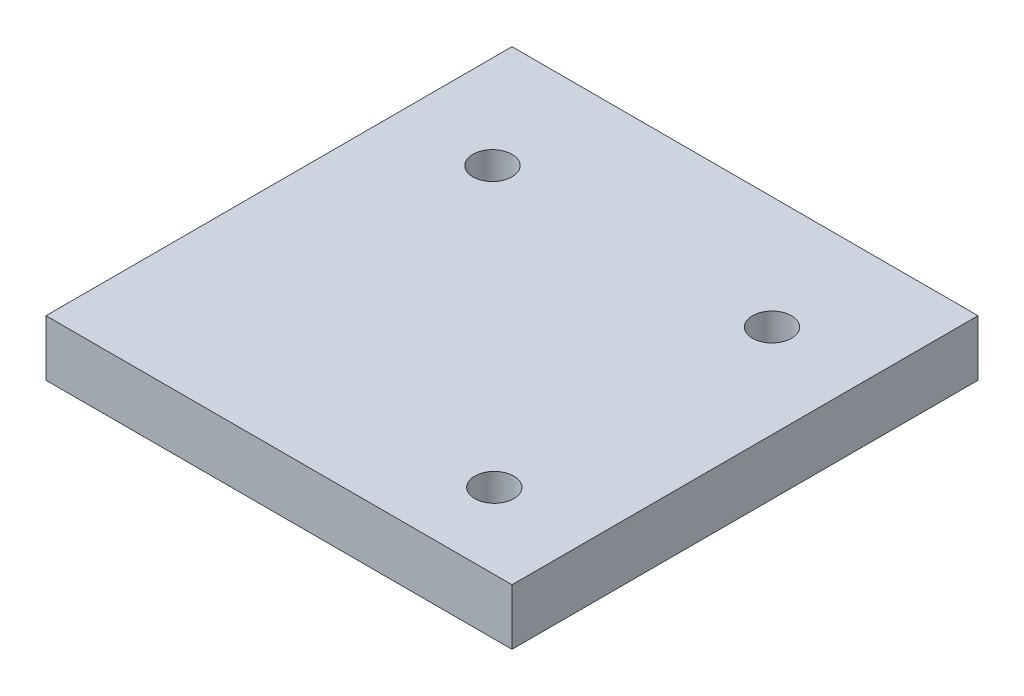
SolidWorks part; units mm, degrees
ref_plane "前视基准面" through (0, 0, 0) normal (0, 0, 1) x (1, 0, 0)
ref_plane "上视基准面" through (0, 0, 0) normal (0, 1, 0) x (1, 0, 0)
ref_plane "右视基准面" through (0, 0, 0) normal (1, 0, 0) x (0, 0, -1)
sketch "草图1" plane through (0, 0, 0) normal (0, 1, 0) x (1, 0, 0)
  line L1 (-25, -25) -> (25, -25)
  line L2 (-25, -25) -> (-25, 25)
  line L3 (-25, 25) -> (25, 25)
  line L4 (25, -25) -> (25, 25)
  line L5 (-25, -25) -> (25, 25) construction
  line L6 (-25, 25) -> (25, -25) construction
  point P0 (0, 0)
  dimension "D1" = 50
  dimension "D2" = 50
extrude "凸台-拉伸1" add sketch "草图1" along normal blind 6
sketch "草图2" plane through (0, 6, 0) normal (0, 1, 0) x (1, 0, 0)
  line L0 (-25, 12.9) -> (25, 12.9) construction
  line L1 (-25, 25) -> (-25, -25) construction
  line L2 (25, -25) -> (25, 25) construction
  line L3 (25, 25) -> (-25, 25) construction
  circle A0 centre (-15, 12.9) radius 2.1
  circle A1 centre (15, 12.9) radius 2.1
  dimension "D4" = 4.2
  dimension "D5" = 4.2
  dimension "D1" = 12.1
  dimension "D2" = 10
  dimension "D3" = 10
extrude "切除-拉伸1" cut sketch "草图2" against normal up to next
sketch "草图3" plane through (0, 6, 0) normal (0, 1, 0) x (1, 0, 0)
  line L0 (15, 12.9) -> (15, -25) construction
  line L1 (-25, -25) -> (25, -25) construction
  circle A0 centre (15, -16.9) radius 2.1
  dimension "D2" = 4.2
  dimension "D1" = 29.8
extrude "切除-拉伸2" cut sketch "草图3" against normal up to next
